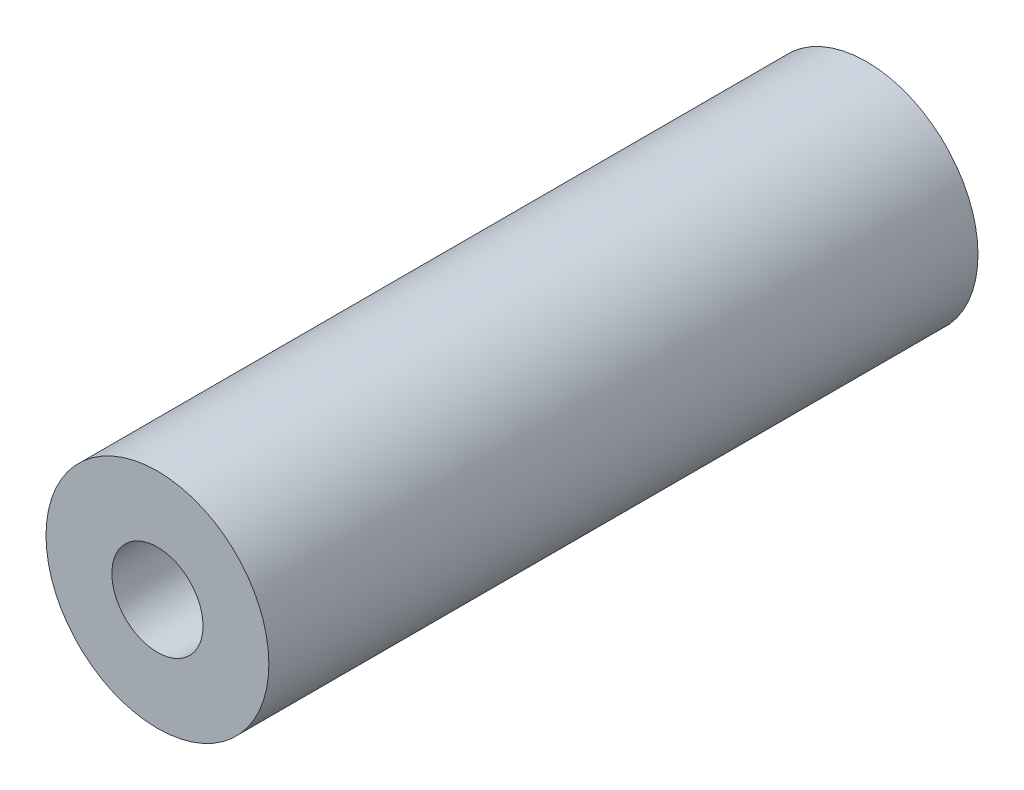
SolidWorks part; units mm, degrees
ref_plane "Front Plane" through (0, 0, 0) normal (0, 0, 1) x (1, 0, 0)
ref_plane "Top Plane" through (0, 0, 0) normal (0, 1, 0) x (1, 0, 0)
ref_plane "Right Plane" through (0, 0, 0) normal (1, 0, 0) x (0, 0, -1)
sketch "Sketch1" plane through (0, 0, 0) normal (0, 0, 1) x (1, 0, 0)
  circle A0 centre (0, 0) radius 2.25
  circle A1 centre (0, 0) radius 5.5
  dimension "D1" = 4.5
  dimension "D2" = 11
extrude "Boss-Extrude1" add sketch "Sketch1" along normal blind 35
